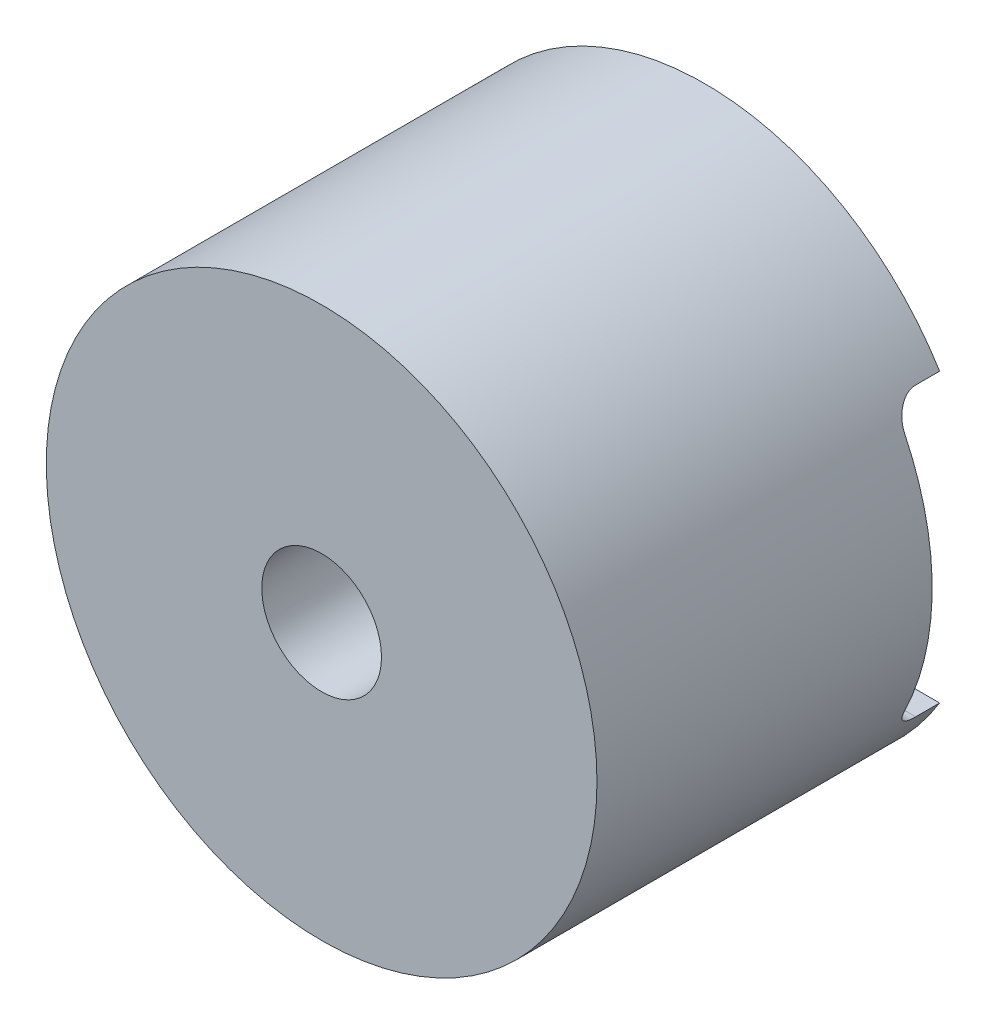
SolidWorks part; units mm, degrees
ref_plane "Ebene vorne" through (0, 0, 0) normal (1, 0, 0) x (0, 1, 0)
ref_plane "Ebene oben" through (0, 0, 0) normal (0, 0, 1) x (0, 1, 0)
ref_plane "Ebene rechts" through (0, 0, 0) normal (0, 1, 0) x (-1, 0, 0)
sketch "Skizze1" plane through (0, 0, 0) normal (0, 0, 1) x (0, 1, 0)
  circle A0 centre (0, 0) radius 5.75
  dimension "D1" = 11.5
extrude "Aufsatz-Linear austragen1" add sketch "Skizze1" along normal blind 8
sketch "Skizze2" plane through (0, 0, 0) normal (0, 0, -1) x (1, 0, 0)
  circle A0 centre (0, 0) radius 4.5
  dimension "D1" = 9
extrude "Schnitt-Linear austragen1" cut sketch "Skizze2" against normal blind 1 contours A0
sketch "Skizze3" plane through (0, 0, 0) normal (0, 0, -1) x (1, 0, 0)
  line L1 (-6.6796, -3) -> (6.6796, -3)
  line L2 (-6.6796, -3) -> (-6.6796, 3)
  line L3 (-6.6796, 3) -> (6.6796, 3)
  line L4 (6.6796, -3) -> (6.6796, 3)
  line L5 (-6.6796, -3) -> (6.6796, 3) construction
  line L6 (-6.6796, 3) -> (6.6796, -3) construction
  point P0 (0, 0)
  dimension "D1" = 6
extrude "Schnitt-Linear austragen2" cut sketch "Skizze3" against normal blind 1
fillet "Verrundung1" radius 0.5 4 edges at (4.1297, 3, 1) (-4.1297, 3, 1) (-4.1297, -3, 1) (4.1297, -3, 1)
sketch "Skizze4" plane through (0, 0, 8) normal (0, 0, 1) x (1, 0, 0)
  circle A0 centre (0, 0) radius 1.25
  dimension "D1" = 2.5
extrude "Schnitt-Linear austragen3" cut sketch "Skizze4" against normal blind 3
sketch "Skizze5" plane through (0, 0, 1) normal (0, 0, -1) x (1, 0, 0)
  circle A0 centre (0, 0) radius 4.5
  dimension "D1" = 9
extrude "Schnitt-Linear austragen4" cut sketch "Skizze5" against normal blind 1 contours A0
